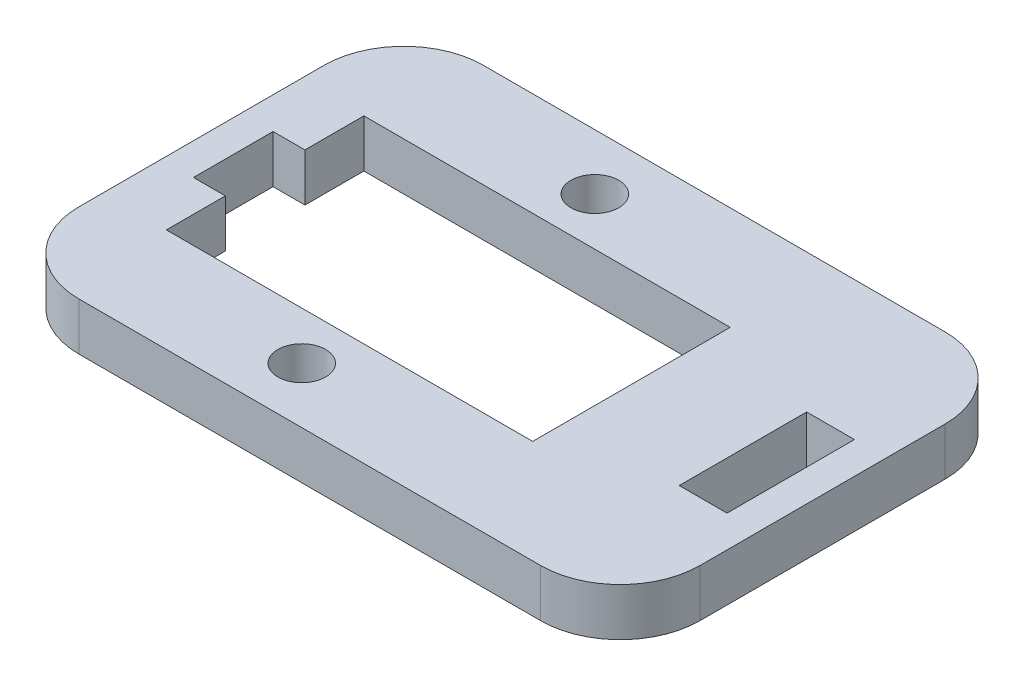
SolidWorks part; units mm, degrees
material "Cedro"
ref_plane "Plano frontal" through (0, 0, 0) normal (0, 0, 1) x (1, 0, 0)
ref_plane "Plano superior" through (0, 0, 0) normal (0, 1, 0) x (1, 0, 0)
ref_plane "Plano direito" through (0, 0, 0) normal (1, 0, 0) x (0, 0, -1)
sketch "Esboço1" plane through (0, 0, 0) normal (0, 1, 0) x (1, 0, 0)
  line L0 (0, 0) -> (23, 0)
  line L1 (23, 0) -> (23, -12.4)
  line L2 (23, -12.4) -> (0, -12.4)
  line L3 (0, 0) -> (0, -3.7)
  line L4 (0, -12.4) -> (0, -8.7)
  line L5 (0, -3.7) -> (-2, -3.7)
  line L6 (-2, -3.7) -> (-2, -8.7)
  line L7 (-2, -8.7) -> (0, -8.7)
  line L9 (30, -6.2) -> (30, -2.2)
  line L10 (30, -2.2) -> (33, -2.2)
  line L11 (33, -2.2) -> (33, -10.2)
  line L12 (33, -10.2) -> (30, -10.2)
  line L13 (30, -10.2) -> (30, -6.2)
  line L17 (11.5, 6.5) -> (1, 6.5)
  line L18 (-4, 1.5) -> (-4, -13.9)
  line L19 (1, -18.9) -> (30, -18.9)
  line L20 (35, -13.9) -> (35, 1.5)
  line L21 (30, 6.5) -> (11.5, 6.5)
  circle A0 centre (11.5, 3) radius 1.5
  arc A1 (-4, 1.5) -> (1, 6.5) centre (1, 1.5) cw
  circle A2 centre (11.5, -15.4) radius 1.5
  arc A3 (35, 1.5) -> (30, 6.5) centre (30, 1.5) ccw
  arc A4 (30, -18.9) -> (35, -13.9) centre (30, -13.9) ccw
  arc A5 (-4, -13.9) -> (1, -18.9) centre (1, -13.9) ccw
  dimension "D1" = 5
  dimension "D2" = 5
  dimension "D3" = 5
  dimension "D4" = 5
extrude "Ressalto-extrusão1" add sketch "Esboço1" along normal blind 3
